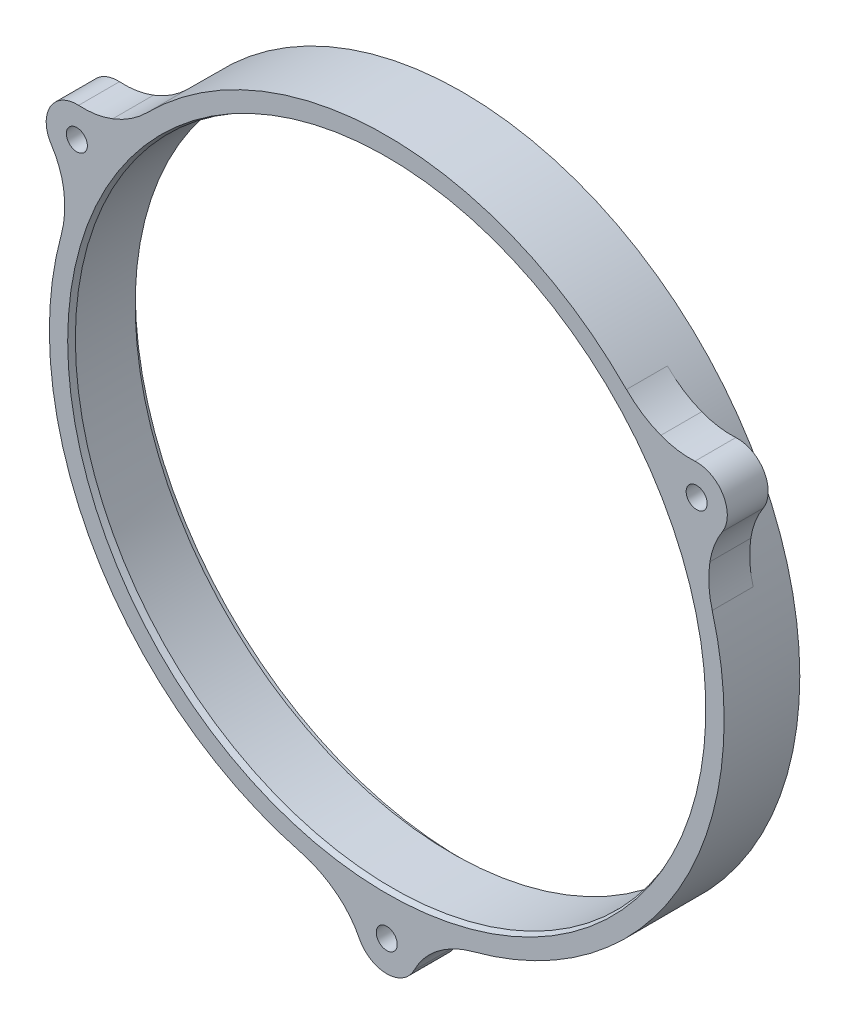
SolidWorks part; units mm, degrees
material "6061-T6 (SS)"
ref_plane "Front Plane" through (0, 0, 0) normal (0, 0, 1) x (1, 0, 0)
ref_plane "Top Plane" through (0, 0, 0) normal (0, 1, 0) x (1, 0, 0)
ref_plane "Right Plane" through (0, 0, 0) normal (1, 0, 0) x (0, 0, -1)
sketch "Sketch3" plane through (0, 0, 0) normal (1, 0, 0) x (0, 0, -1)
  line L2 (0, 104.775) -> (23.495, 104.775)
  line L3 (23.495, 104.775) -> (23.495, 101.6)
  line L4 (20.32, 98.4504) -> (0, 98.4504)
  line L5 (0, 98.4504) -> (0, 104.775)
  line L6 (23.495, 101.6) -> (20.32, 101.6)
  line L7 (20.32, 101.6) -> (20.32, 98.4504)
  line L8 (0, 0) -> (50000, 0) construction
  dimension "D1" = 196.9008
  dimension "D2" = 209.55
  dimension "D4" = 3.175
  dimension "D6" = 3.175
  dimension "D7" = 20.32
revolve "Revolve1" add sketch "Sketch3" angle 360 about L8
sketch "Sketch8" plane through (0, 0, 0) normal (0, 0, 1) x (1, 0, 0)
  line L0 (0, 5.7357) -> (0, 39864.8487) construction
  line L1 (-69.2295, 39.9697) -> (30448.5125, -17579.4569) construction
  arc A0 (-95.702, 65.0725) -> (-104.2054, 50.3441) centre (-96.2371, 55.5625) ccw
  arc A2 (-100.3578, 40.344) -> (-104.2054, 50.3441) centre (-125.4542, 36.4284) ccw
  arc A3 (-100.3578, 40.344) -> (-101.071, 27.6125) centre (-130.4735, 35.6453) cw
  arc A5 (-85.1178, 66.7404) -> (-74.4487, 73.7238) centre (-96.1064, 95.1707) ccw
  arc A6 (-85.1178, 66.7404) -> (-95.702, 65.0725) centre (-94.275, 90.4323) cw
  arc A7 (-74.4487, 73.7238) -> (-101.071, 27.6125) centre (0, 0) ccw
  circle A8 centre (0, 0) radius 104.775 construction
  dimension "D1" = 25.4
  dimension "D2" = 111.125
  dimension "D3" = 30.48
  dimension "D4" = 9.525
  dimension "D6" = 30.48
  dimension "D5" = 60
extrude "Boss-Extrude2" add sketch "Sketch8" against normal blind 12.7
hole_wizard "1/4 Clearance Hole1" positions "Sketch7" profile "Sketch6" hole size "1/4" standard "Ansi Inch" end condition through all
sketch "Sketch7" plane through (-78.913, -32.7479, 0) normal (0, 0, 1) x (1, 0, 0)
  arc A0 (-16.789, 97.8203) -> (-25.2924, 83.092) centre (-17.3241, 88.3104) ccw construction
  point P0 (-17.3241, 88.3104)
sketch "Sketch6" plane through (-96.2371, 55.5625, 0) normal (1, 0, 0) x (0, -1, 0)
  line L0 (0, 0) -> (0, 23.495)
  line L1 (0, 23.495) -> (3.2639, 23.495)
  line L2 (3.2639, 23.495) -> (3.2639, 0)
  line L5 (3.2639, 0) -> (0, 0)
  line L11 (0, -6.35) -> (0, 107.95) construction
  dimension "Thru Hole Dia." = 6.5278
  dimension "Thru Hole Depth" = 23.495
pattern_circular "CirPattern3" count 3 over 360 about axis through (0, 0, 0) along (0, 0, 1) of "Boss-Extrude2", "1/4 Clearance Hole1"
chamfer "Chamfer1" distance 0.635 angle 70 1 edges at (98.4504, 0, 0)
